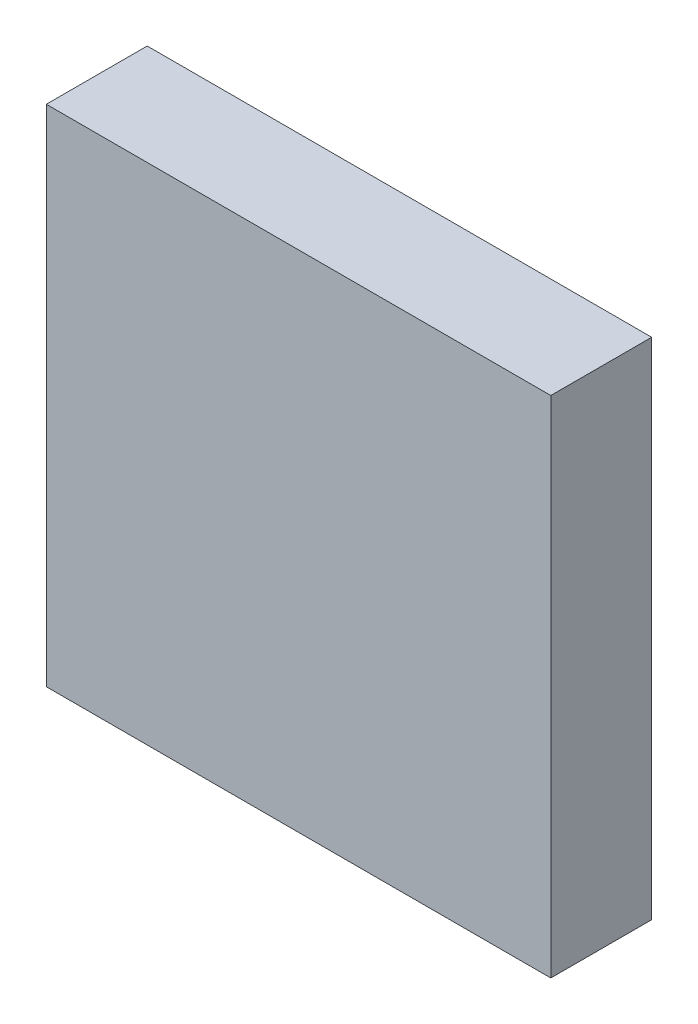
SolidWorks part; units mm, degrees
ref_plane "Front Plane" through (0, 0, 0) normal (0, 0, 1) x (1, 0, 0)
ref_plane "Top Plane" through (0, 0, 0) normal (0, 1, 0) x (1, 0, 0)
ref_plane "Right Plane" through (0, 0, 0) normal (1, 0, 0) x (0, 0, -1)
ref_plane "电池贴合面" through (0, 0, 1.6) normal (0, 0, 1) x (1, 0, 0)
sketch "电池本体_草图" plane through (0, 0, 1.6) normal (0, 0, 1) x (1, 0, 0)
  line L1 (0, -50) -> (30, -50)
  line L2 (0, -50) -> (0, -20)
  line L3 (0, -20) -> (30, -20)
  line L4 (30, -50) -> (30, -20)
  dimension "D1" = 30
  dimension "D2" = 30
extrude "电池本体" add sketch "电池本体_草图" along normal blind 6
ref_plane "刻字面" through (0, 0, 1.6) normal (0, 0, 1) x (1, 0, 0)
sketch "刻字_电池_草图" plane through (0, 0, 1.6) normal (0, 0, 1) x (1, 0, 0)
  line L0 (16.6022, -31.3327) -> (16.6022, -36.8616)
  line L1 (16.6022, -36.8616) -> (16.4318, -36.9307)
  line L2 (16.4318, -36.9307) -> (16.2496, -36.999)
  line L3 (16.2496, -36.999) -> (16.0554, -37.0664)
  line L4 (16.0554, -37.0664) -> (15.8494, -37.1329)
  line L5 (15.8494, -37.1329) -> (15.6316, -37.1986)
  line L6 (15.6316, -37.1986) -> (15.4018, -37.2635)
  line L7 (15.4018, -37.2635) -> (15.4995, -37.8207)
  line L8 (15.4995, -37.8207) -> (15.6092, -38.2989)
  line L9 (15.6092, -38.2989) -> (15.7312, -38.6979)
  line L10 (15.7312, -38.6979) -> (15.8653, -39.0177)
  line L11 (15.8653, -39.0177) -> (16.0115, -39.2585)
  line L12 (16.0115, -39.2585) -> (16.1699, -39.4201)
  line L13 (16.1699, -39.4201) -> (16.3433, -39.532)
  line L14 (16.3433, -39.532) -> (16.5344, -39.6236)
  line L15 (16.5344, -39.6236) -> (16.7434, -39.6948)
  line L16 (16.7434, -39.6948) -> (16.9702, -39.7457)
  line L17 (16.9702, -39.7457) -> (17.2147, -39.7762)
  line L18 (17.2147, -39.7762) -> (17.4771, -39.7864)
  line L19 (17.4771, -39.7864) -> (19.9186, -39.7864)
  line L20 (19.9186, -39.7864) -> (20.4253, -39.7445)
  line L21 (20.4253, -39.7445) -> (20.8398, -39.6191)
  line L22 (20.8398, -39.6191) -> (21.1623, -39.41)
  line L23 (21.1623, -39.41) -> (21.3926, -39.1172)
  line L24 (21.3926, -39.1172) -> (21.5307, -38.7408)
  line L25 (21.5307, -38.7408) -> (21.5768, -38.2808)
  line L26 (21.5768, -38.2808) -> (21.5768, -37.2635)
  line L27 (21.5768, -37.2635) -> (23.5707, -37.2635)
  line L28 (23.5707, -37.2635) -> (23.5707, -38.057)
  line L29 (23.5707, -38.057) -> (25.0356, -38.057)
  line L30 (25.0356, -38.057) -> (25.0356, -31.3327)
  line L31 (25.0356, -31.3327) -> (21.5768, -31.3327)
  line L32 (21.5768, -31.3327) -> (21.5768, -30.0814)
  line L33 (21.5768, -30.0814) -> (20.1017, -30.0814)
  line L34 (20.1017, -30.0814) -> (20.1017, -31.3327)
  line L35 (20.1017, -31.3327) -> (16.6022, -31.3327)
  line L36 (18.0671, -32.6144) -> (20.1017, -32.6144)
  line L37 (20.1017, -32.6144) -> (20.1017, -33.6521)
  line L38 (20.1017, -33.6521) -> (18.0671, -33.6521)
  line L39 (18.0671, -33.6521) -> (18.0671, -32.6144)
  line L40 (23.5707, -32.6144) -> (23.5707, -33.6521)
  line L41 (23.5707, -33.6521) -> (21.5768, -33.6521)
  line L42 (21.5768, -33.6521) -> (21.5768, -32.6144)
  line L43 (21.5768, -32.6144) -> (23.5707, -32.6144)
  line L44 (18.0671, -35.9817) -> (18.0671, -34.9339)
  line L45 (18.0671, -34.9339) -> (20.1017, -34.9339)
  line L46 (20.1017, -34.9339) -> (20.1017, -35.9817)
  line L47 (20.1017, -35.9817) -> (18.0671, -35.9817)
  line L48 (23.5707, -35.9817) -> (21.5768, -35.9817)
  line L49 (21.5768, -35.9817) -> (21.5768, -34.9339)
  line L50 (21.5768, -34.9339) -> (23.5707, -34.9339)
  line L51 (23.5707, -34.9339) -> (23.5707, -35.9817)
  line L52 (19.4812, -38.5249) -> (17.9552, -38.5249)
  line L53 (17.9552, -38.5249) -> (17.8342, -38.5213)
  line L54 (17.8342, -38.5213) -> (17.7218, -38.5105)
  line L55 (17.7218, -38.5105) -> (17.6183, -38.4925)
  line L56 (17.6183, -38.4925) -> (17.5235, -38.4673)
  line L57 (17.5235, -38.4673) -> (17.4374, -38.4349)
  line L58 (17.4374, -38.4349) -> (17.3601, -38.3952)
  line L59 (17.3601, -38.3952) -> (17.2915, -38.3493)
  line L60 (17.2915, -38.3493) -> (17.2315, -38.298)
  line L61 (17.2315, -38.298) -> (17.1802, -38.2414)
  line L62 (17.1802, -38.2414) -> (17.1374, -38.1793)
  line L63 (17.1374, -38.1793) -> (17.1033, -38.1119)
  line L64 (17.1033, -38.1119) -> (17.0778, -38.0392)
  line L65 (17.0778, -38.0392) -> (17.0559, -37.9547)
  line L66 (17.0559, -37.9547) -> (17.0323, -37.8524)
  line L67 (17.0323, -37.8524) -> (17.0072, -37.7321)
  line L68 (17.0072, -37.7321) -> (16.9806, -37.5938)
  line L69 (16.9806, -37.5938) -> (16.9524, -37.4376)
  line L70 (16.9524, -37.4376) -> (16.9227, -37.2635)
  line L71 (16.9227, -37.2635) -> (20.1017, -37.2635)
  line L72 (20.1017, -37.2635) -> (20.1017, -37.9858)
  line L73 (20.1017, -37.9858) -> (20.0845, -38.1505)
  line L74 (20.0845, -38.1505) -> (20.0328, -38.2853)
  line L75 (20.0328, -38.2853) -> (19.9466, -38.3901)
  line L76 (19.9466, -38.3901) -> (19.8259, -38.465)
  line L77 (19.8259, -38.465) -> (19.6708, -38.5099)
  line L78 (19.6708, -38.5099) -> (19.4812, -38.5249)
  line L79 (5.4832, -31.5666) -> (5.498, -32.6642)
  line L80 (5.498, -32.6642) -> (5.5151, -33.5967)
  line L81 (5.5151, -33.5967) -> (5.5347, -34.3642)
  line L82 (5.5347, -34.3642) -> (5.5567, -34.9667)
  line L83 (5.5567, -34.9667) -> (5.5811, -35.4041)
  line L84 (5.5811, -35.4041) -> (5.6078, -35.6765)
  line L85 (5.6078, -35.6765) -> (5.6418, -35.8589)
  line L86 (5.6418, -35.8589) -> (5.6878, -36.0263)
  line L87 (5.6878, -36.0263) -> (5.7458, -36.1788)
  line L88 (5.7458, -36.1788) -> (5.8158, -36.3163)
  line L89 (5.8158, -36.3163) -> (5.8978, -36.4388)
  line L90 (5.8978, -36.4388) -> (5.9919, -36.5463)
  line L91 (5.9919, -36.5463) -> (6.1173, -36.6394)
  line L92 (6.1173, -36.6394) -> (6.2937, -36.7187)
  line L93 (6.2937, -36.7187) -> (6.5209, -36.7841)
  line L94 (6.5209, -36.7841) -> (6.7989, -36.8357)
  line L95 (6.7989, -36.8357) -> (7.1278, -36.8734)
  line L96 (7.1278, -36.8734) -> (7.5076, -36.8973)
  line L97 (7.5076, -36.8973) -> (7.5596, -36.6706)
  line L98 (7.5596, -36.6706) -> (7.6139, -36.4451)
  line L99 (7.6139, -36.4451) -> (7.6704, -36.2208)
  line L100 (7.6704, -36.2208) -> (7.7292, -35.9975)
  line L101 (7.7292, -35.9975) -> (7.7902, -35.7754)
  line L102 (7.7902, -35.7754) -> (7.8535, -35.5544)
  line L103 (7.8535, -35.5544) -> (7.605, -35.5644)
  line L104 (7.605, -35.5644) -> (7.3952, -35.5638)
  line L105 (7.3952, -35.5638) -> (7.2241, -35.5525)
  line L106 (7.2241, -35.5525) -> (7.0917, -35.5307)
  line L107 (7.0917, -35.5307) -> (6.998, -35.4983)
  line L108 (6.998, -35.4983) -> (6.943, -35.4552)
  line L109 (6.943, -35.4552) -> (6.9104, -35.3533)
  line L110 (6.9104, -35.3533) -> (6.8837, -35.1441)
  line L111 (6.8837, -35.1441) -> (6.8629, -34.8277)
  line L112 (6.8629, -34.8277) -> (6.8481, -34.404)
  line L113 (6.8481, -34.404) -> (6.8392, -33.8731)
  line L114 (6.8392, -33.8731) -> (6.8362, -33.235)
  line L115 (6.8362, -33.235) -> (8.0163, -33.5148)
  line L116 (8.0163, -33.5148) -> (8.0163, -38.0061)
  line L117 (8.0163, -38.0061) -> (9.3998, -38.0061)
  line L118 (9.3998, -38.0061) -> (9.3998, -33.8403)
  line L119 (9.3998, -33.8403) -> (10.4069, -34.0743)
  line L120 (10.4069, -34.0743) -> (10.4069, -38.0061)
  line L121 (10.4069, -38.0061) -> (10.3911, -38.1864)
  line L122 (10.3911, -38.1864) -> (10.3436, -38.3339)
  line L123 (10.3436, -38.3339) -> (10.2645, -38.4486)
  line L124 (10.2645, -38.4486) -> (10.1537, -38.5306)
  line L125 (10.1537, -38.5306) -> (10.0113, -38.5797)
  line L126 (10.0113, -38.5797) -> (9.8372, -38.5961)
  line L127 (9.8372, -38.5961) -> (7.3652, -38.5961)
  line L128 (7.3652, -38.5961) -> (7.2104, -38.5903)
  line L129 (7.2104, -38.5903) -> (7.0713, -38.573)
  line L130 (7.0713, -38.573) -> (6.9481, -38.544)
  line L131 (6.9481, -38.544) -> (6.8407, -38.5034)
  line L132 (6.8407, -38.5034) -> (6.7492, -38.4513)
  line L133 (6.7492, -38.4513) -> (6.6734, -38.3876)
  line L134 (6.6734, -38.3876) -> (6.6076, -38.2894)
  line L135 (6.6076, -38.2894) -> (6.5457, -38.1338)
  line L136 (6.5457, -38.1338) -> (6.4878, -37.9209)
  line L137 (6.4878, -37.9209) -> (6.4338, -37.6506)
  line L138 (6.4338, -37.6506) -> (6.3838, -37.323)
  line L139 (6.3838, -37.323) -> (6.3377, -36.9379)
  line L140 (6.3377, -36.9379) -> (6.1103, -37.0385)
  line L141 (6.1103, -37.0385) -> (5.8822, -37.1369)
  line L142 (5.8822, -37.1369) -> (5.6536, -37.233)
  line L143 (5.6536, -37.233) -> (5.4244, -37.3268)
  line L144 (5.4244, -37.3268) -> (5.1947, -37.4183)
  line L145 (5.1947, -37.4183) -> (4.9644, -37.5076)
  line L146 (4.9644, -37.5076) -> (5.0543, -37.9652)
  line L147 (5.0543, -37.9652) -> (5.1543, -38.3647)
  line L148 (5.1543, -38.3647) -> (5.2645, -38.7061)
  line L149 (5.2645, -38.7061) -> (5.3849, -38.9895)
  line L150 (5.3849, -38.9895) -> (5.5154, -39.2148)
  line L151 (5.5154, -39.2148) -> (5.6562, -39.382)
  line L152 (5.6562, -39.382) -> (5.8085, -39.5087)
  line L153 (5.8085, -39.5087) -> (5.9738, -39.6123)
  line L154 (5.9738, -39.6123) -> (6.1521, -39.6929)
  line L155 (6.1521, -39.6929) -> (6.3434, -39.7505)
  line L156 (6.3434, -39.7505) -> (6.5477, -39.785)
  line L157 (6.5477, -39.785) -> (6.765, -39.7965)
  line L158 (6.765, -39.7965) -> (10.2543, -39.7965)
  line L159 (10.2543, -39.7965) -> (10.7237, -39.7499)
  line L160 (10.7237, -39.7499) -> (11.1077, -39.61)
  line L161 (11.1077, -39.61) -> (11.4064, -39.3769)
  line L162 (11.4064, -39.3769) -> (11.6198, -39.0505)
  line L163 (11.6198, -39.0505) -> (11.7478, -38.6309)
  line L164 (11.7478, -38.6309) -> (11.7904, -38.118)
  line L165 (11.7904, -38.118) -> (11.7904, -34.3998)
  line L166 (11.7904, -34.3998) -> (12.3805, -34.5371)
  line L167 (12.3805, -34.5371) -> (12.6755, -33.2248)
  line L168 (12.6755, -33.2248) -> (11.7904, -33.0214)
  line L169 (11.7904, -33.0214) -> (11.7904, -30.9054)
  line L170 (11.7904, -30.9054) -> (10.4069, -30.9054)
  line L171 (10.4069, -30.9054) -> (10.4069, -32.706)
  line L172 (10.4069, -32.706) -> (9.3998, -32.472)
  line L173 (9.3998, -32.472) -> (9.3998, -30)
  line L174 (9.3998, -30) -> (8.0163, -30)
  line L175 (8.0163, -30) -> (8.0163, -32.1516)
  line L176 (8.0163, -32.1516) -> (5.4832, -31.5666)
  line L177 (14.0793, -30.1424) -> (13.8143, -30.3286)
  line L178 (13.8143, -30.3286) -> (13.5413, -30.5279)
  line L179 (13.5413, -30.5279) -> (13.2604, -30.7401)
  line L180 (13.2604, -30.7401) -> (12.9716, -30.9653)
  line L181 (12.9716, -30.9653) -> (12.6749, -31.2035)
  line L182 (12.6749, -31.2035) -> (12.3703, -31.4547)
  line L183 (12.3703, -31.4547) -> (13.3062, -32.4924)
  line L184 (13.3062, -32.4924) -> (13.5806, -32.2375)
  line L185 (13.5806, -32.2375) -> (13.8544, -31.9882)
  line L186 (13.8544, -31.9882) -> (14.1277, -31.7447)
  line L187 (14.1277, -31.7447) -> (14.4004, -31.5067)
  line L188 (14.4004, -31.5067) -> (14.6725, -31.2744)
  line L189 (14.6725, -31.2744) -> (14.944, -31.0478)
  line L190 (14.944, -31.0478) -> (14.0793, -30.1424)
  line L191 (14.1913, -32.8484) -> (13.8937, -33.0621)
  line L192 (13.8937, -33.0621) -> (13.6046, -33.2757)
  line L193 (13.6046, -33.2757) -> (13.324, -33.4893)
  line L194 (13.324, -33.4893) -> (13.0519, -33.703)
  line L195 (13.0519, -33.703) -> (12.7882, -33.9166)
  line L196 (12.7882, -33.9166) -> (12.5331, -34.1302)
  line L197 (12.5331, -34.1302) -> (13.5198, -35.1882)
  line L198 (13.5198, -35.1882) -> (13.736, -34.9774)
  line L199 (13.736, -34.9774) -> (13.9708, -34.7587)
  line L200 (13.9708, -34.7587) -> (14.2243, -34.532)
  line L201 (14.2243, -34.532) -> (14.4964, -34.2975)
  line L202 (14.4964, -34.2975) -> (14.7872, -34.055)
  line L203 (14.7872, -34.055) -> (15.0966, -33.8047)
  line L204 (15.0966, -33.8047) -> (14.1913, -32.8484)
  line L205 (13.7945, -35.5951) -> (13.5351, -35.7062)
  line L206 (13.5351, -35.7062) -> (13.2859, -35.8087)
  line L207 (13.2859, -35.8087) -> (13.0468, -35.9028)
  line L208 (13.0468, -35.9028) -> (12.8179, -35.9885)
  line L209 (12.8179, -35.9885) -> (12.5992, -36.0656)
  line L210 (12.5992, -36.0656) -> (12.3906, -36.1343)
  line L211 (12.3906, -36.1343) -> (12.5625, -36.7136)
  line L212 (12.5625, -36.7136) -> (12.7456, -37.3189)
  line L213 (12.7456, -37.3189) -> (12.94, -37.9502)
  line L214 (12.94, -37.9502) -> (13.1457, -38.6074)
  line L215 (13.1457, -38.6074) -> (13.3627, -39.2907)
  line L216 (13.3627, -39.2907) -> (13.591, -40)
  line L217 (13.591, -40) -> (15.0051, -39.532)
  line L218 (15.0051, -39.532) -> (14.785, -38.9056)
  line L219 (14.785, -38.9056) -> (14.5722, -38.2672)
  line L220 (14.5722, -38.2672) -> (14.3667, -37.617)
  line L221 (14.3667, -37.617) -> (14.1686, -36.9549)
  line L222 (14.1686, -36.9549) -> (13.9779, -36.2809)
  line L223 (13.9779, -36.2809) -> (13.7945, -35.5951)
extrude "刻字_电池" cut sketch "刻字_电池_草图" along normal blind 0.3
